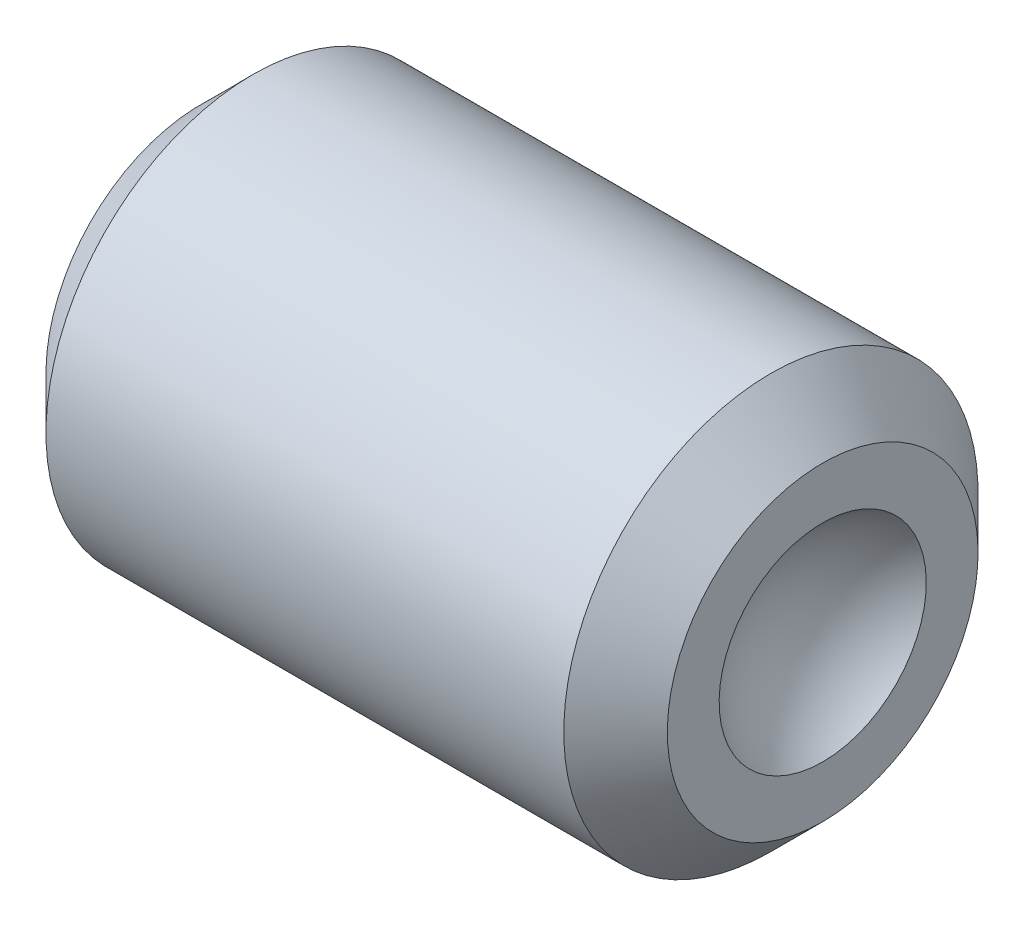
SolidWorks part; units mm, degrees
ref_plane "Front Plane" through (0, 0, 0) normal (0, 0, 1) x (1, 0, 0)
ref_plane "Top Plane" through (0, 0, 0) normal (0, 1, 0) x (1, 0, 0)
ref_plane "Right Plane" through (0, 0, 0) normal (1, 0, 0) x (0, 0, -1)
sketch "Sketch1" plane through (0, 0, 0) normal (0, 0, 1) x (1, 0, 0)
  line L0 (0, 0) -> (0, 1.5)
  line L1 (0, 1.5) -> (0.5, 2)
  line L2 (0.5, 2) -> (5.5, 2)
  line L3 (5.5, 2) -> (6, 1.5)
  line L4 (0, 0) -> (5.5, 0) construction
  line L5 (0.5, 2) -> (0.5, 1.5) construction
  line L6 (0.5, 1.5) -> (0.5, 1) construction
  line L7 (0.5, 1) -> (0.5, 0.5) construction
  line L8 (0.5, 0.5) -> (0.5, 0) construction
  line L9 (0.5, 1.5) -> (0, 1.5) construction
  line L10 (5.5, 2) -> (5.5, 0) construction
  line L11 (6, 1.5) -> (6, 1)
  line L12 (0, 0) -> (5.5, 0)
  arc A0 (5.5, 0) -> (6, 1) centre (6.75, 0) cw
  dimension "D1" = 45
  dimension "D2" = 4
  dimension "D3" = 6
  dimension "D4" = 2
revolve "Revolve1" add sketch "Sketch1" angle 360 about L12
sketch "Sketch2" plane through (0, 0, 0) normal (-1, 0, 0) x (0, 0, 1)
  line L1 (0, 1.1547) -> (-1, 0.5774)
  line L2 (-1, 0.5774) -> (-1, -0.5774)
  line L3 (-1, -0.5774) -> (0, -1.1547)
  line L4 (0, -1.1547) -> (1, -0.5774)
  line L5 (1, -0.5774) -> (1, 0.5774)
  line L6 (1, 0.5774) -> (0, 1.1547)
  circle A0 centre (0, 0) radius 1 construction
  dimension "D1" = 2
extrude "Cut-Extrude1" cut sketch "Sketch2" against normal offset from surface (4 mm away) 2 up to face at (6, -1.5, 0)
